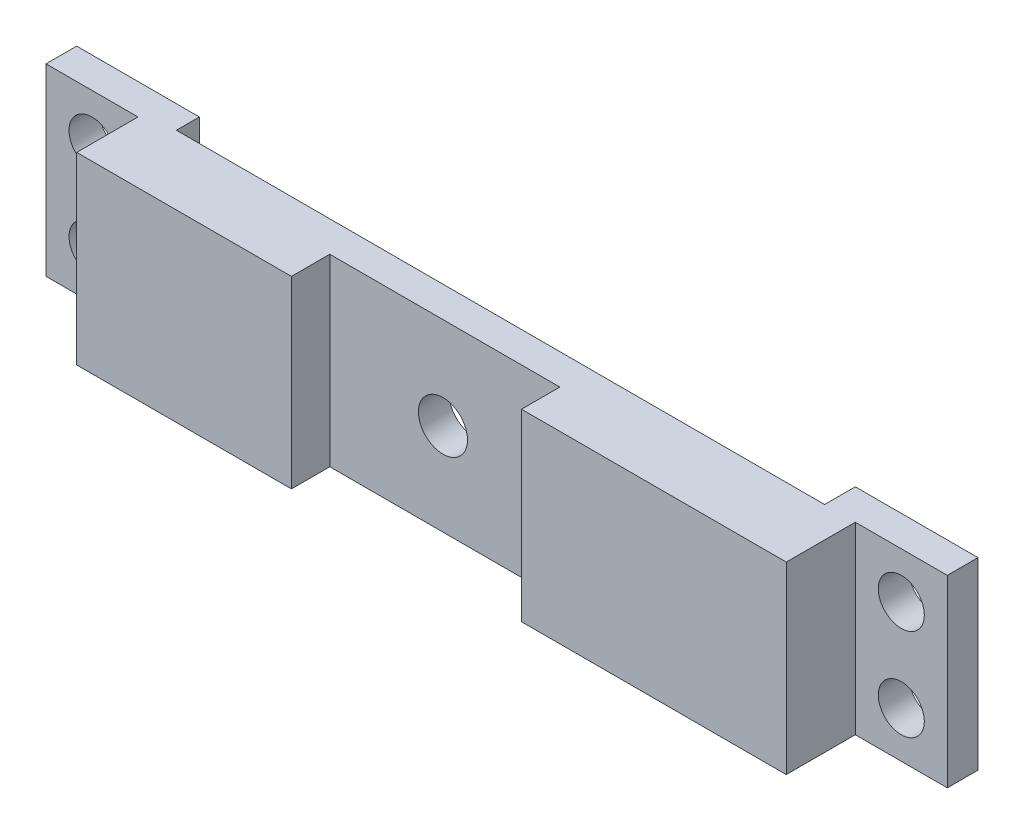
SolidWorks part; units mm, degrees
ref_plane "Front" through (0, 0, 0) normal (0, 0, 1) x (1, 0, 0)
ref_plane "Top" through (0, 0, 0) normal (0, 1, 0) x (1, 0, 0)
ref_plane "Right" through (0, 0, 0) normal (1, 0, 0) x (0, 0, -1)
sketch "Sketch1" plane through (0, 0, 0) normal (0, 0, 1) x (1, 0, 0)
  line L1 (-17.5, 6) -> (17.5, 6)
  line L2 (-17.5, 6) -> (-17.5, -6)
  line L3 (-17.5, -6) -> (17.5, -6)
  line L4 (17.5, 6) -> (17.5, -6)
  dimension "D1" = 12
  dimension "D2" = 35
  dimension "D3" = 17.5
  dimension "D4" = 6
extrude "Extrude1" add sketch "Sketch1" along normal blind 6
sketch "Sketch2" plane through (0, 0, 6) normal (0, 0, 1) x (1, 0, 0)
  line L0 (-17.5, -6) -> (17.5, -6) construction
  line L1 (-17.5, 6) -> (-11.5, 6)
  line L2 (-17.5, 6) -> (-17.5, -6)
  line L3 (-17.5, -6) -> (-11.5, -6)
  line L4 (-11.5, 6) -> (-11.5, -6)
  dimension "D1" = 6
extrude "Extrude2" cut sketch "Sketch2" against normal blind 4
sketch "Sketch3" plane through (0, 0, 2) normal (0, 0, 1) x (1, 0, 0)
  line L0 (-17.5, 6) -> (-17.5, -6) construction
  line L1 (-17.5, -6) -> (-11.5, -6) construction
  line L2 (-11.5, 6) -> (-17.5, 6) construction
  circle A0 centre (-14.5, 3) radius 1.5
  circle A1 centre (-14.5, -3) radius 1.5
  dimension "D1" = 3
  dimension "D2" = 3
  dimension "D5" = 3
  dimension "D3" = 3
  dimension "D4" = 3
  dimension "D6" = 3
extrude "Extrude3" cut sketch "Sketch3" against normal up to surface (2 mm away) up to face at (0, 0, 0)
sketch "Sketch4" plane through (0, 0, 6) normal (0, 0, 1) x (1, 0, 0)
  line L0 (17.5, -6) -> (17.5, 6) construction
  circle A0 centre (9.88, 0) radius 1.6
  dimension "D1" = 3.2
  dimension "D2" = 7.62
extrude "Extrude4" cut sketch "Sketch4" against normal up to surface (6 mm away) up to face at (-13, -3, 0)
sketch "Sketch7" plane through (0, 0, 6) normal (0, 0, 1) x (1, 0, 0)
  line L0 (-11.5, -6) -> (17.5, -6) construction
  line L1 (17.5, 6) -> (2.5, 6)
  line L2 (17.5, 6) -> (17.5, -6)
  line L3 (17.5, -6) -> (2.5, -6)
  line L4 (2.5, 6) -> (2.5, -6)
  dimension "D1" = 15
extrude "Extrude6" cut sketch "Sketch7" against normal blind 2.5
sketch "Sketch8" plane through (0, 0, 0) normal (0, 0, -1) x (-1, 0, 0)
  line L0 (17.5, -6) -> (-17.5, -6) construction
  line L1 (-17.5, 6) -> (9.5, 6)
  line L2 (-17.5, 6) -> (-17.5, -6)
  line L3 (-17.5, -6) -> (9.5, -6)
  line L4 (9.5, 6) -> (9.5, -6)
  dimension "D1" = 27
extrude "Extrude7" cut sketch "Sketch8" against normal blind 1.5
sketch "Sketch9" plane through (17.5, 0, 0) normal (1, 0, 0) x (0, 0, -1)
  line L1 (-6, 6) -> (-1.5, 6)
  line L2 (-6, 6) -> (-6, -6)
  line L3 (-6, -6) -> (-1.5, -6)
  line L4 (-1.5, 6) -> (-1.5, -6)
extrude "Extrude8" add sketch "Sketch9" along normal blind 17.26
sketch "Sketch10" plane through (0, 6, 0) normal (0, 1, 0) x (1, 0, 0)
  line L0 (-9.5, -1.5) -> (34.76, -1.5) construction
  line L1 (32.76, -1.5) -> (40.76, -1.5)
  line L2 (32.76, -1.5) -> (32.76, 0.5)
  line L3 (32.76, 0.5) -> (40.76, 0.5)
  line L4 (40.76, -1.5) -> (40.76, 0.5)
  line L5 (34.76, -1.5) -> (34.76, -6) construction
  dimension "D1" = 2
  dimension "D2" = 2
  dimension "D3" = 8
extrude "Extrude9" add sketch "Sketch10" against normal up to surface (12 mm away) up to face at (2.085, -6, 3.2708)
sketch "Sketch12" plane through (0, 0, 1.5) normal (0, 0, 1) x (1, 0, 0)
  line L0 (34.76, 6) -> (40.76, 6) construction
  line L1 (40.76, -6) -> (40.76, 6) construction
  line L3 (40.76, -6) -> (34.76, -6) construction
  circle A0 centre (37.76, 3) radius 1.5
  circle A1 centre (37.76, -3) radius 1.5
  dimension "D1" = 3
  dimension "D2" = 3
  dimension "D4" = 3
  dimension "D6" = 3
  dimension "D3" = 3
  dimension "D5" = 3
extrude "Extrude10" cut sketch "Sketch12" against normal up to surface (2 mm away) up to face at (36.76, 0, -0.5)
